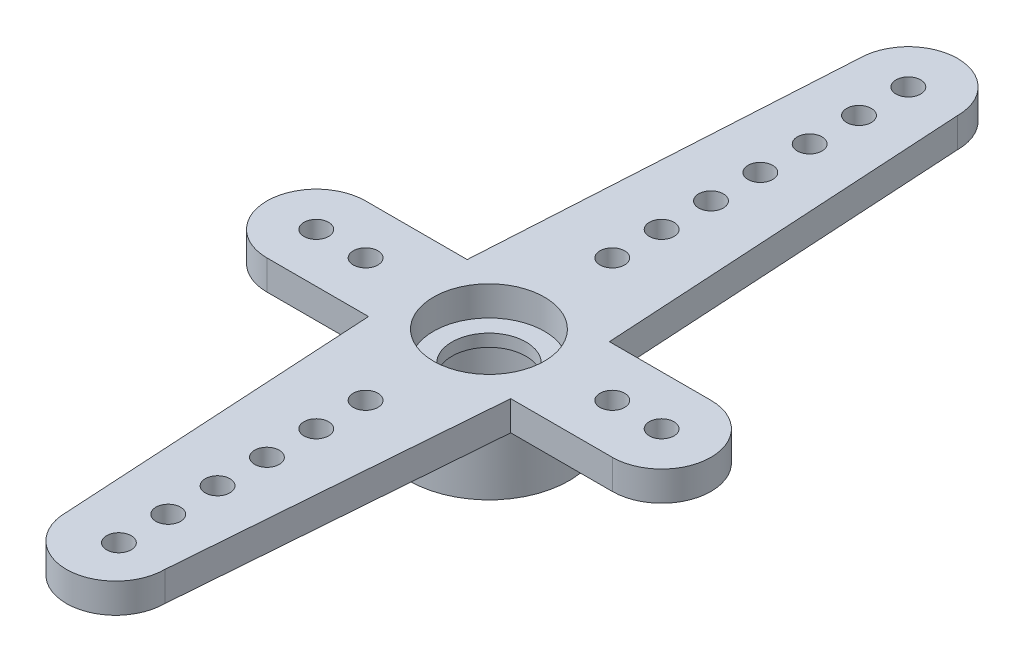
SolidWorks part; units mm, degrees
ref_plane "Front Plane" through (0, 0, 0) normal (0, 0, 1) x (1, 0, 0)
ref_plane "Top Plane" through (0, 0, 0) normal (0, 1, 0) x (1, 0, 0)
ref_plane "Right Plane" through (0, 0, 0) normal (1, 0, 0) x (0, 0, -1)
sketch "Sketch1" plane through (0, 0, 0) normal (0, 1, 0) x (1, 0, 0)
  line L0 (0, 0) -> (0, 17) construction
  line L3 (-2.8824, 2) -> (-2, 17)
  line L4 (2.8824, 2) -> (2, 17)
  line L5 (-3, 0) -> (3, 0) construction
  line L6 (-2.8824, -2) -> (-2.1324, -14.9994)
  line L7 (2.8824, -2) -> (1.8676, -15)
  line L8 (0, 0) -> (7, 0) construction
  line L9 (2.8824, 2) -> (7, 2)
  line L10 (2.8824, -2) -> (7, -2)
  line L11 (-2.8824, -2) -> (-7, -2)
  line L12 (-2.8824, 2) -> (-7, 2)
  arc A3 (2, 17) -> (-2, 17) centre (0, 17) ccw
  circle A4 centre (0, 5) radius 0.5
  circle A5 centre (0, 7) radius 0.5
  circle A6 centre (0, 9) radius 0.5
  circle A7 centre (0, 11) radius 0.5
  circle A8 centre (0, 13) radius 0.5
  circle A9 centre (0, 15) radius 0.5
  circle A10 centre (0, 17) radius 0.5
  circle A12 centre (0, -15) radius 0.5
  circle A13 centre (0, -13) radius 0.5
  circle A14 centre (0, -11) radius 0.5
  circle A15 centre (0, -9) radius 0.5
  circle A16 centre (0, -7) radius 0.5
  circle A17 centre (0, -5) radius 0.5
  arc A18 (1.8676, -15) -> (-2.1324, -14.9994) centre (-0.1324, -14.9994) cw
  arc A20 (7, -2) -> (7, 2) centre (7, 0) ccw
  circle A21 centre (7, 0) radius 0.5
  circle A22 centre (5, 0) radius 0.5
  circle A23 centre (-5, 0) radius 0.5
  circle A24 centre (-7, 0) radius 0.5
  arc A25 (-7, -2) -> (-7, 2) centre (-7, 0) cw
  circle A26 centre (0, 0) radius 2.25
  point P3 (0, 17.0297)
  point P38 (0, -17.0297)
  point P39 (3.5, 0)
  dimension "D2" = 2
  dimension "D5" = 1
  dimension "D8" = 2
  dimension "D10" = 1
  dimension "D11" = 1
  dimension "D13" = 4.5
  dimension "D15" = 2
  dimension "D1" = 1
  dimension "D3" = 17
  dimension "D4" = 1
  dimension "D6" = 5
  dimension "D9" = 7
  dimension "D12" = 2
  dimension "D14" = 15
  dimension "D16" = 0.75
  dimension "D7" = 7
extrude "Boss-Extrude1" add sketch "Sketch1" along normal blind 1.2
sketch "Sketch2" plane through (0, 0, 0) normal (0, 1, 0) x (1, 0, 0)
  circle A0 centre (0, 0) radius 1.5
  circle A1 centre (0, 0) radius 3.25
  dimension "D1" = 3
  dimension "D2" = 6.5
extrude "Boss-Extrude2" add sketch "Sketch2" against normal blind 2.5
sketch "Sketch3" plane through (0, -2.5, 0) normal (0, -1, 0) x (1, 0, 0)
  circle A0 centre (0, 0) radius 2.5
  dimension "D1" = 5
extrude "Cut-Extrude1" cut sketch "Sketch3" against normal blind 2
